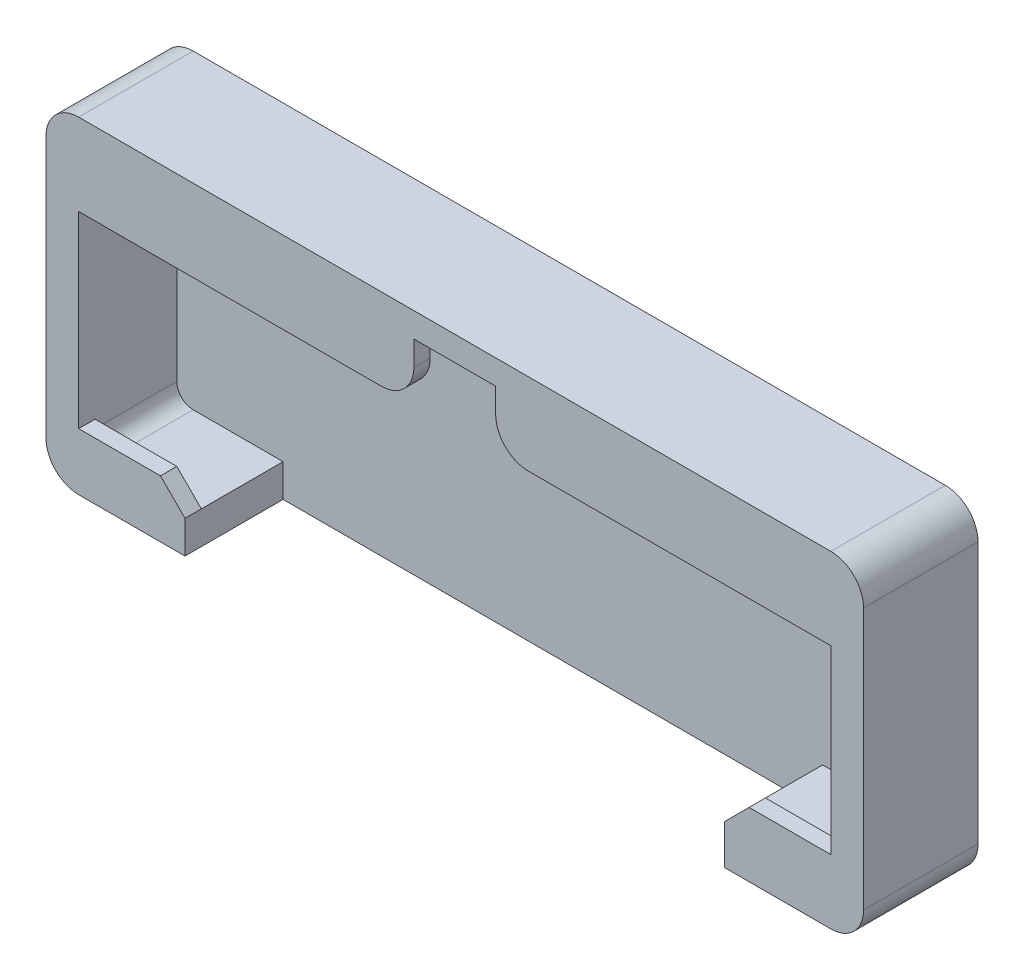
SolidWorks part; units mm, degrees
ref_plane "Front Plane" through (0, 0, 0) normal (0, 0, 1) x (1, 0, 0)
ref_plane "Top Plane" through (0, 0, 0) normal (0, 1, 0) x (1, 0, 0)
ref_plane "Right Plane" through (0, 0, 0) normal (1, 0, 0) x (0, 0, -1)
sketch "Sketch1" plane through (0, 0, 0) normal (0, 0, 1) x (1, 0, 0)
  line L1 (-25, 10) -> (25, 10)
  line L2 (-25, 10) -> (-25, -10)
  line L3 (-25, -10) -> (25, -10)
  line L4 (25, 10) -> (25, -10)
  line L5 (-25, 10) -> (25, -10) construction
  line L6 (-25, -10) -> (25, 10) construction
  point P0 (0, 0)
  dimension "D1" = 50
  dimension "D2" = 20
extrude "Boss-Extrude1" add sketch "Sketch1" along normal blind 1
sketch "Sketch2" plane through (0, 0, 1) normal (0, 0, 1) x (1, 0, 0)
  line L0 (25, -10) -> (25, 10) construction
  line L1 (-25, 10) -> (25, 10)
  line L2 (-25, 10) -> (-25, 9)
  line L3 (-23, 9) -> (23, 9)
  line L4 (25, 10) -> (25, 9)
  line L5 (-25, -10) -> (25, -10) construction
  line L7 (-25, 9) -> (-25, -10)
  line L8 (-25, -10) -> (-23, -10)
  line L9 (-23, 9) -> (-23, -10)
  line L12 (25, 9) -> (25, -10)
  line L13 (25, -10) -> (23, -10)
  line L14 (23, 9) -> (23, -10)
  dimension "D1" = 1
  dimension "D2" = 2
  dimension "D3" = 2
extrude "Boss-Extrude2" add sketch "Sketch2" along normal blind 6
sketch "Sketch3" plane through (0, 9, 0) normal (0, -1, 0) x (1, 0, 0)
  line L0 (23, 7) -> (23, 1) construction
  line L1 (-23, 7) -> (23, 7)
  line L2 (-23, 7) -> (-23, 6)
  line L3 (-23, 6) -> (23, 6)
  line L4 (23, 7) -> (23, 6)
  dimension "D1" = 1
extrude "Boss-Extrude3" add sketch "Sketch3" along normal blind 4
sketch "Sketch4" plane through (0, 0, 1) normal (0, 0, 1) x (1, 0, 0)
  line L0 (23, 5) -> (-23, 5) construction
  line L1 (-23, -10) -> (-16.5, -10)
  line L2 (-23, -10) -> (-23, -8)
  line L3 (-23, -8) -> (-16.5, -8)
  line L4 (-16.5, -10) -> (-16.5, -8)
  line L5 (23, -10) -> (16.5, -10)
  line L6 (23, -10) -> (23, -7.5612)
  line L7 (23, -7.5612) -> (16.5, -7.5612)
  line L8 (16.5, -10) -> (16.5, -7.5612)
  dimension "D1" = 33
  dimension "D2" = 6.5
  dimension "D3" = 13
extrude "Boss-Extrude4" add sketch "Sketch4" along normal blind 6
sketch "Sketch5" plane through (0, -8, 0) normal (0, 1, 0) x (1, 0, 0)
  line L0 (-23, -7) -> (-23, -1) construction
  line L1 (-16.5, -7) -> (-23, -7)
  line L2 (-16.5, -7) -> (-16.5, -6)
  line L3 (-16.5, -6) -> (-23, -6)
  line L4 (-23, -7) -> (-23, -6)
  dimension "D1" = 1
extrude "Boss-Extrude5" add sketch "Sketch5" along normal blind 1.5
sketch "Sketch6" plane through (0, -7.5612, 0) normal (0, 1, 0) x (1, 0, 0)
  line L0 (23, -7) -> (23, -1) construction
  line L1 (16.5, -7) -> (23, -7)
  line L2 (16.5, -7) -> (16.5, -6)
  line L3 (16.5, -6) -> (23, -6)
  line L4 (23, -7) -> (23, -6)
  dimension "D1" = 1
extrude "Boss-Extrude6" add sketch "Sketch6" along normal blind 1.5
chamfer "Chamfer1" distance 1.5 angle 45 2 edges at (16.5, -6.0612, 6.5) (-16.5, -6.5, 6.5)
fillet "Fillet1" radius 2 4 edges at (-25, -10, 3.5) (25, -10, 3.5) (25, 10, 3.5) (-25, 10, 3.5)
fillet "Fillet2" radius 1 4 edges at (-23, -8, 3.5) (23, -7.5612, 3.5) (23, 9, 3.5) (-23, 9, 3.5)
sketch "Sketch7" plane through (0, 0, 7) normal (0, 0, 1) x (1, 0, 0)
  line L0 (23, 5) -> (-23, 5) construction
  line L1 (-2.5, 8.5) -> (2.5, 8.5)
  line L2 (-2.5, 8.5) -> (-2.5, 5)
  line L3 (-2.5, 5) -> (2.5, 5)
  line L4 (2.5, 8.5) -> (2.5, 5)
  line L5 (-2.5, 8.5) -> (2.5, 5) construction
  line L6 (-2.5, 5) -> (2.5, 8.5) construction
  line L7 (23, 10) -> (-23, 10) construction
  point P0 (0, 6.75)
  dimension "D1" = 5
  dimension "D2" = 0
  dimension "D3" = 1.5
extrude "Cut-Extrude1" cut sketch "Sketch7" against normal blind 2
fillet "Fillet3" radius 2 2 edges at (-2.5, 5, 6.5) (2.5, 5, 6.5)
